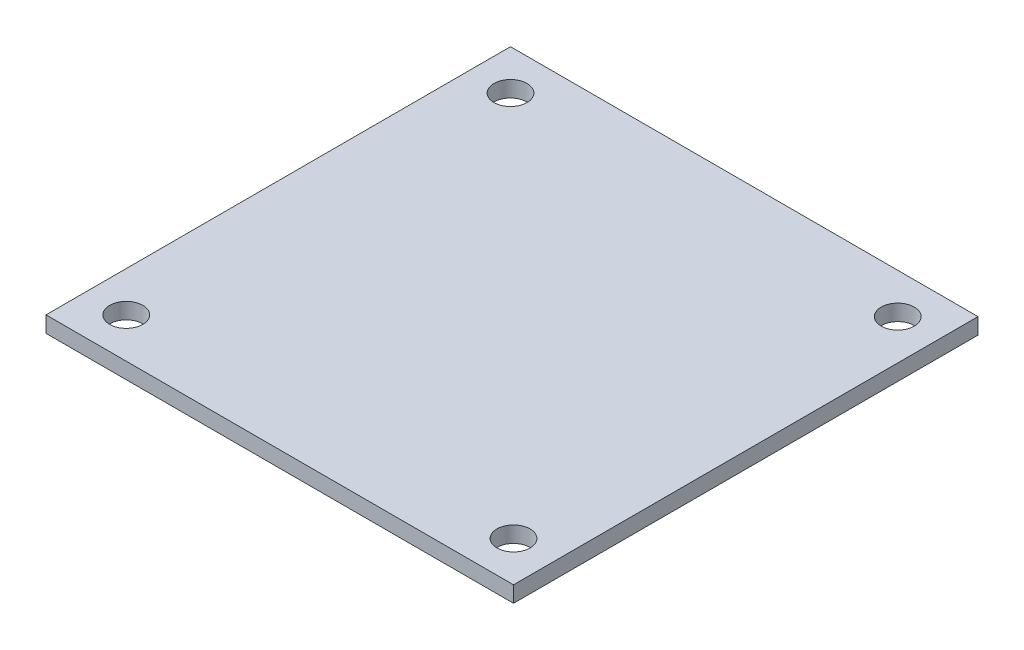
SolidWorks part; units mm, degrees
ref_plane "Front Plane" through (0, 0, 0) normal (0, 0, 1) x (1, 0, 0)
ref_plane "Top Plane" through (0, 0, 0) normal (0, 1, 0) x (1, 0, 0)
ref_plane "Right Plane" through (0, 0, 0) normal (1, 0, 0) x (0, 0, -1)
sketch "Sketch1" plane through (0, 0, 0) normal (0, 1, 0) x (1, 0, 0)
  line L1 (-7.9845, -21.895) -> (38.6155, -21.895)
  line L2 (-7.9845, -21.895) -> (-7.9845, 24.405)
  line L3 (-7.9845, 24.405) -> (38.6155, 24.405)
  line L4 (38.6155, -21.895) -> (38.6155, 24.405)
  line L5 (-7.9845, -21.895) -> (38.6155, 24.405) construction
  line L6 (-7.9845, 24.405) -> (38.6155, -21.895) construction
  point P4 (15.3155, 1.255)
extrude "Boss-Extrude1" add sketch "Sketch1" along normal blind 1.6
sketch "Sketch2" plane through (0, 0, 0) normal (0, -1, 0) x (1, 0, 0)
  line L0 (-7.9845, -24.405) -> (-7.9845, 21.895) construction
  line L1 (38.6155, -24.405) -> (-7.9845, -24.405) construction
  circle A0 centre (-3.9845, -20.405) radius 1.65
  dimension "D1" = 4
  dimension "D2" = 4
ref_plane "Plane7" through (15.3155, 0, 0) normal (1, 0, 0) x (0, 0, -1)
ref_plane "Plane8" through (0, 0, -1.255) normal (0, 0, -1) x (-1, 0, 0)
extrude "Cut-Extrude1" cut sketch "Sketch2" against normal through all contours A0
mirror "Mirror1" about plane through (15.3155, 0, 0) normal (1, 0, 0) of "Cut-Extrude1"
mirror "Mirror3" about plane through (0, 0, -1.255) normal (0, 0, -1) of "Mirror1", "Cut-Extrude1"
equation "\"MDF\"= 4.8mm"
equation "\"Foamcore\"= 4.6mm"
equation "\"GMaterial\"= \"MDF\""
